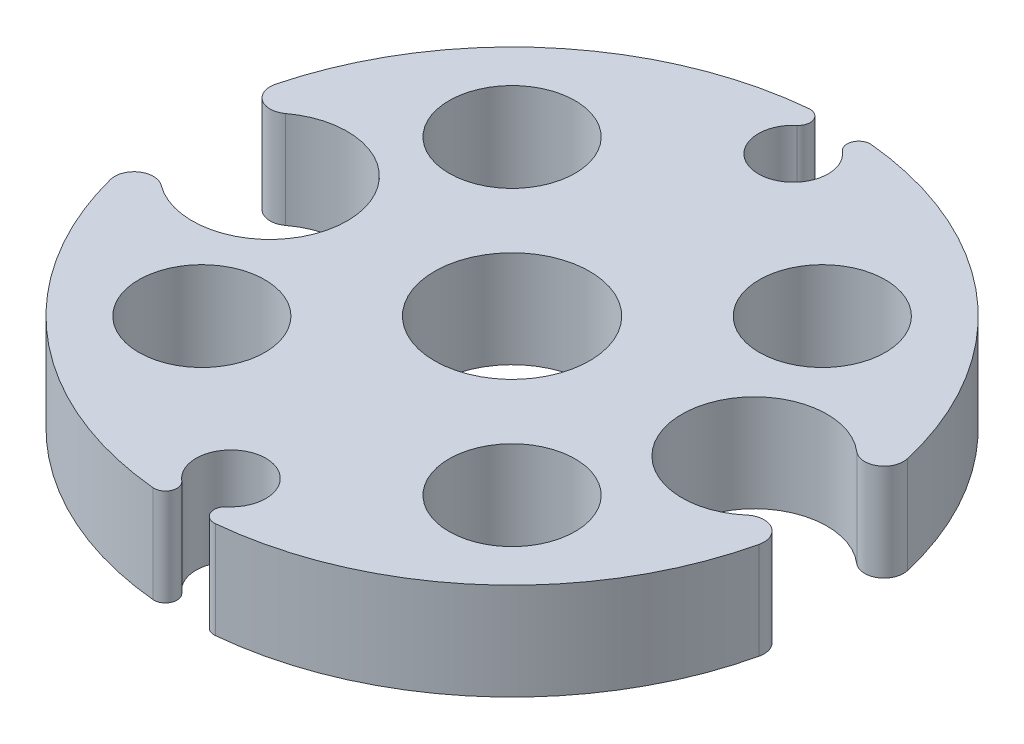
SolidWorks part; units mm, degrees
material "Acrylic (Medium-high impact)"
ref_plane "Front Plane" through (0, 0, 0) normal (0, 0, 1) x (1, 0, 0)
ref_plane "Top Plane" through (0, 0, 0) normal (0, 1, 0) x (1, 0, 0)
ref_plane "Right Plane" through (0, 0, 0) normal (1, 0, 0) x (0, 0, -1)
sketch "Sketch2" plane through (0, 0, 0) normal (0, 1, 0) x (1, 0, 0)
  line L0 (76.4675, 97.4227) -> (101.4675, 97.4227) construction
  line L1 (88.9675, 111.9227) -> (88.9675, 82.9227) construction
  line L2 (88.9675, 97.4227) -> (68.2874, 76.7426) construction
  arc A0 (74.0755, 100.6287) -> (72.5094, 101.6807) centre (73.4775, 101.4302) cw
  circle A1 centre (80.9675, 89.4227) radius 3.25
  arc A2 (103.9064, 100.2598) -> (105.5327, 101.2429) centre (104.5583, 101.0181) ccw
  arc A3 (74.0755, 94.2167) -> (72.5094, 93.1648) centre (73.4775, 93.4153) ccw
  arc A4 (87.3529, 114.3459) -> (72.5094, 101.6807) centre (88.9675, 97.4227) ccw
  arc A5 (103.9064, 94.5856) -> (105.5327, 93.6026) centre (104.5583, 93.8273) cw
  arc A6 (87.7993, 113.2921) -> (90.1292, 113.2977) centre (88.9675, 111.9227) ccw
  arc A7 (87.7993, 113.2921) -> (87.3529, 114.3459) centre (87.4099, 113.7486) ccw
  arc A8 (90.5703, 114.347) -> (90.1292, 113.2977) centre (90.514, 113.7533) ccw
  arc A9 (90.1357, 81.5533) -> (87.8058, 81.5478) centre (88.9675, 82.9227) ccw
  arc A10 (90.1357, 81.5533) -> (90.5821, 80.4996) centre (90.5251, 81.0969) ccw
  arc A11 (87.3647, 80.4985) -> (87.8058, 81.5478) centre (87.4209, 81.0922) ccw
  arc A12 (72.5094, 93.1648) -> (87.3647, 80.4985) centre (88.9675, 97.4227) ccw
  arc A13 (105.5327, 101.2429) -> (90.5703, 114.347) centre (88.9675, 97.4227) ccw
  circle A14 centre (88.9675, 97.4227) radius 4
  arc A15 (74.0755, 94.2167) -> (74.0755, 100.6287) centre (76.4675, 97.4227) ccw
  arc A16 (103.9064, 100.2598) -> (103.9064, 94.5856) centre (101.4675, 97.4227) ccw
  arc A17 (90.5821, 80.4996) -> (105.5327, 93.6026) centre (88.9675, 97.4227) ccw
  circle A18 centre (80.9675, 105.4227) radius 3.25
  circle A19 centre (96.9675, 105.4227) radius 3.25
  circle A20 centre (96.9675, 89.4227) radius 3.25
  point P41 (88.9675, 97.4227)
  point P44 (88.9675, 97.4227)
  point P52 (88.9675, 97.4227)
  dimension "D1" = 14.5
  dimension "D3" = 45
  dimension "D6" = 4
  dimension "D7" = 4
  dimension "D4" = 6.5
  dimension "D5" = 8
  dimension "D9" = 8
  dimension "D10" = 1.8
  dimension "D11" = 34
  dimension "D13" = 0.6
  dimension "D8" = 90
  dimension "D12" = 25
extrude "Boss-Extrude1" add sketch "Sketch2" along normal blind 5
